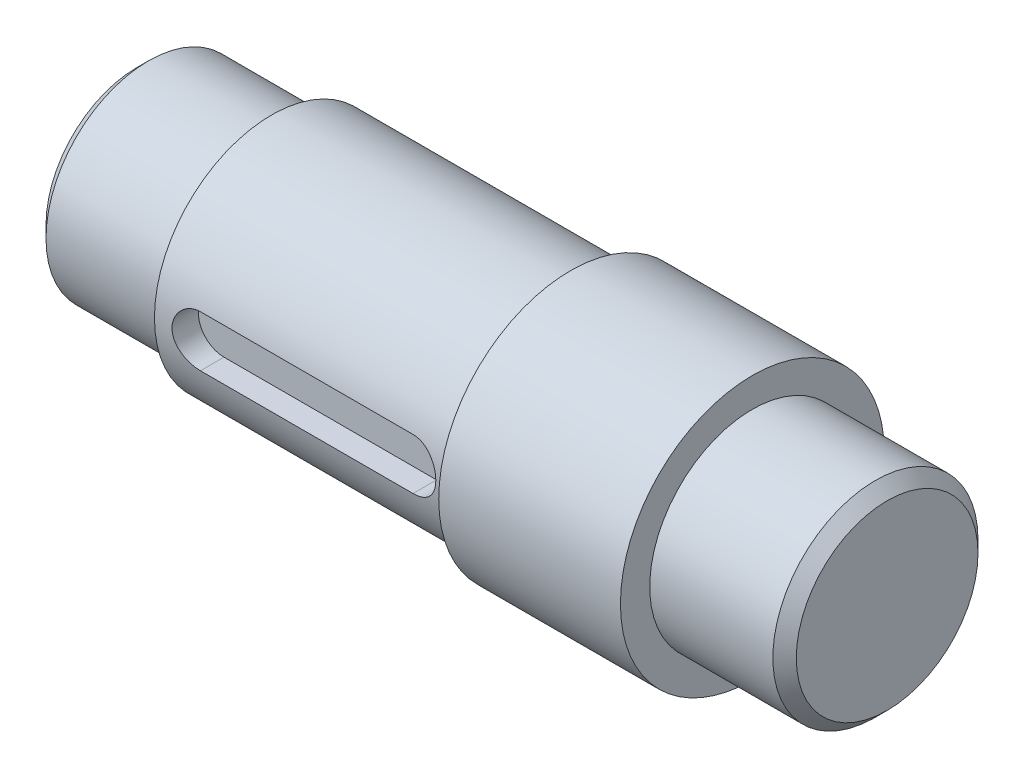
SolidWorks part; units mm, degrees
ref_plane "前视基准面" through (0, 0, 0) normal (0, 0, 1) x (1, 0, 0)
ref_plane "上视基准面" through (0, 0, 0) normal (0, 1, 0) x (1, 0, 0)
ref_plane "右视基准面" through (0, 0, 0) normal (1, 0, 0) x (0, 0, -1)
other "Configuration Table"
sketch "草图1" plane through (0, 0, 0) normal (1, 0, 0) x (0, 0, -1)
  circle A0 centre (0, 0) radius 22.5
  dimension "D1" = 45
extrude "凸台-拉伸1" add sketch "草图1" along normal blind 128
sketch "草图2" plane through (128, 0, 0) normal (1, 0, 0) x (0, 0, -1)
  circle A0 centre (0, 0) radius 17.5
  dimension "D1" = 35
extrude "切除-拉伸1" cut sketch "草图2" against normal blind 23 flip side to cut
sketch "草图3" plane through (0, 0, 0) normal (-1, 0, 0) x (0, 0, 1)
  circle A0 centre (0, 0) radius 20
  dimension "D1" = 40
extrude "切除-拉伸2" cut sketch "草图3" against normal blind 74 flip side to cut
sketch "草图4" plane through (0, 0, 0) normal (-1, 0, 0) x (0, 0, 1)
  circle A0 centre (0, 0) radius 17.5
  dimension "D1" = 35
extrude "切除-拉伸3" cut sketch "草图4" against normal offset from surface (23 mm away) 51 flip side to cut up to face at (74, 0, 20)
sketch "草图5" plane through (0, 0, 0) normal (0, 0, 1) x (1, 0, 0)
  line L0 (30.3626, 0) -> (66.6374, 0) construction
  line L1 (30.3626, 4.3626) -> (66.6374, 4.3626)
  line L2 (30.3626, -4.3626) -> (66.6374, -4.3626)
  line L3 (74, 22.5) -> (74, -22.5) construction
  arc A0 (30.3626, 4.3626) -> (30.3626, -4.3626) centre (30.3626, 0) ccw
  arc A1 (66.6374, -4.3626) -> (66.6374, 4.3626) centre (66.6374, 0) ccw
  point P2 (48.5, 0)
  point P7 (0, 0)
  dimension "D1" = 3
  dimension "D2" = 45
extrude "切除-拉伸4" cut sketch "草图5" along normal through all from offset 15.5
chamfer "倒角1" distance 2 angle 45 2 edges at (0, 0, 17.5) (128, 0, -17.5)
